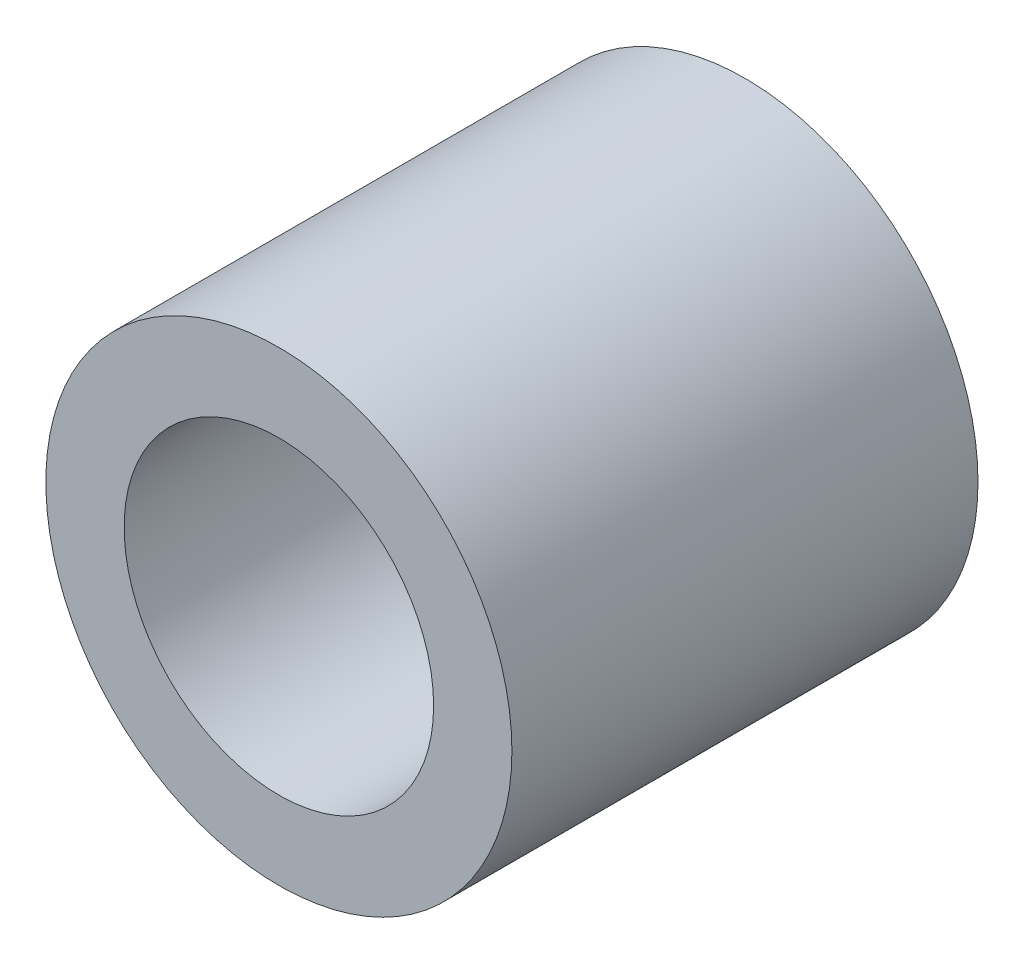
SolidWorks part; units mm, degrees
material "6061-T6 (SS)"
ref_plane "Front Plane" through (0, 0, 0) normal (0, 0, 1) x (1, 0, 0)
ref_plane "Top Plane" through (0, 0, 0) normal (0, 1, 0) x (1, 0, 0)
ref_plane "Right Plane" through (0, 0, 0) normal (1, 0, 0) x (0, 0, -1)
sketch "Sketch1" plane through (0, 0, 0) normal (1, 0, 0) x (0, 0, -1)
  line L0 (-43.4652, 0) -> (107.0331, 0) construction
  line L1 (0, 0) -> (0, 2.1082) construction
  line L2 (-3.175, 3.175) -> (3.175, 3.175)
  line L3 (-3.175, 3.175) -> (-3.175, 2.1082)
  line L4 (-3.175, 2.1082) -> (3.175, 2.1082)
  line L5 (3.175, 3.175) -> (3.175, 2.1082)
  dimension "ID" = 4.2164
  dimension "OD" = 6.35
  dimension "L" = 6.35
revolve "Revolve1" add sketch "Sketch1" angle 360 about L0
